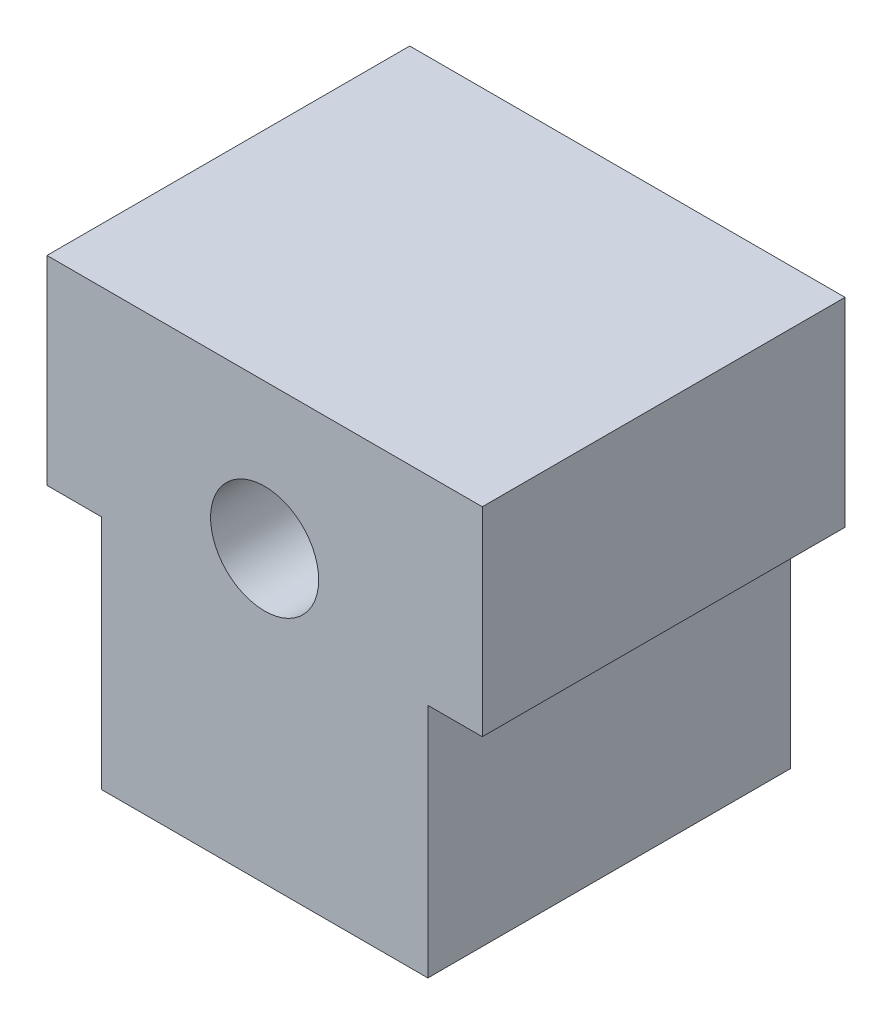
SolidWorks part; units mm, degrees
ref_plane "Front Plane" through (0, 0, 0) normal (0, 0, 1) x (1, 0, 0)
ref_plane "Top Plane" through (0, 0, 0) normal (0, 1, 0) x (1, 0, 0)
ref_plane "Right Plane" through (0, 0, 0) normal (1, 0, 0) x (0, 0, -1)
sketch "Sketch1" plane through (0, 0, 0) normal (0, 0, 1) x (1, 0, 0)
  line L0 (-7.2901, -0.6637) -> (-8.7901, -0.6637)
  line L1 (-8.7901, 4.8263) -> (3.2099, 4.8263)
  line L2 (-8.7901, 4.8263) -> (-8.7901, -0.6637)
  line L3 (-7.2901, -7.1737) -> (1.7099, -7.1737)
  line L4 (3.2099, 4.8263) -> (3.2099, -0.6637)
  line L5 (1.7099, -0.6637) -> (3.2099, -0.6637)
  line L6 (-7.2901, -0.6637) -> (-7.2901, -7.1737)
  line L7 (1.7099, -0.6637) -> (1.7099, -7.1737)
  line L8 (-2.7901, 4.8263) -> (-2.7901, -13.1737) construction
  circle A0 centre (-2.7901, 0.8263) radius 1.49
  point P4 (-5.2878, -0.8927)
  dimension "D2" = 2.98
  dimension "D1" = 4
  dimension "D3" = 12
  dimension "D4" = 6
  dimension "D5" = 12
  dimension "D6" = 1.5
  dimension "D7" = 1.5
extrude "Boss-Extrude1" add sketch "Sketch1" along normal blind 10
